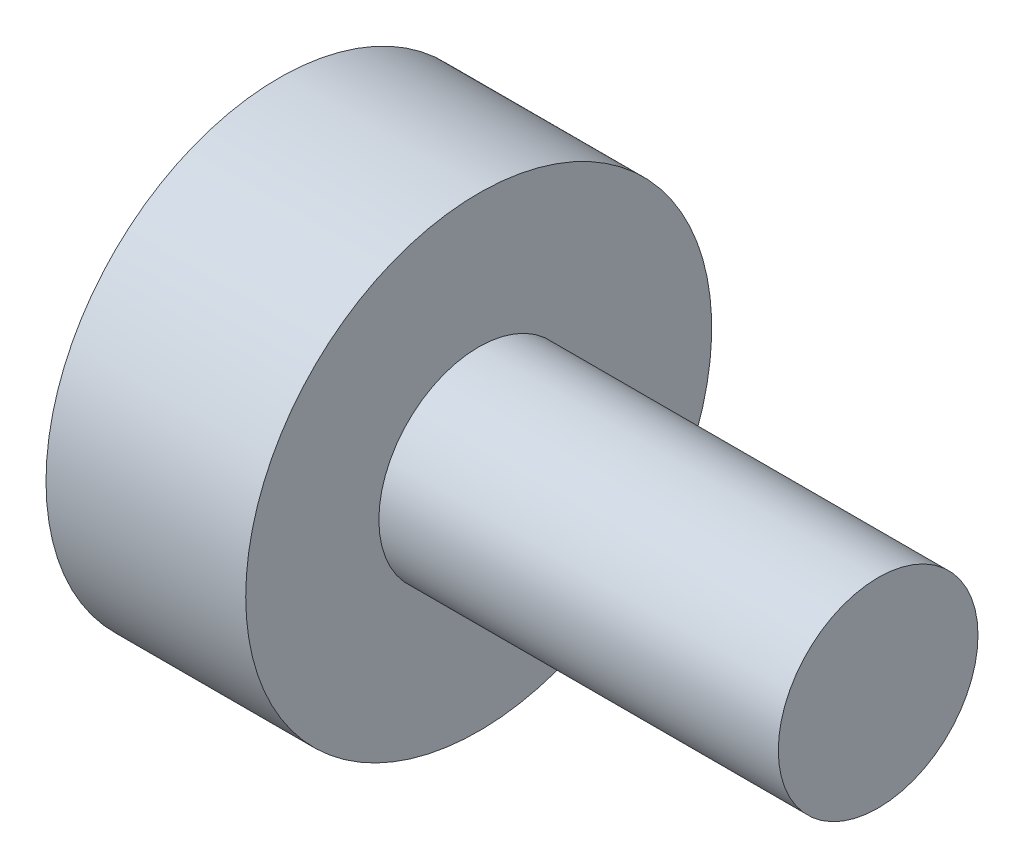
SolidWorks part; units mm, degrees
ref_plane "Спереди" through (0, 0, 0) normal (0, 0, 1) x (1, 0, 0)
ref_plane "Сверху" through (0, 0, 0) normal (0, 1, 0) x (1, 0, 0)
ref_plane "Справа" through (0, 0, 0) normal (1, 0, 0) x (0, 0, -1)
sketch "Эскиз1" plane through (0, 0, 0) normal (0, 0, 1) x (1, 0, 0)
  line L0 (0, 0) -> (100, 0)
  line L1 (0, 0) -> (0, 20)
  line L2 (0, 20) -> (10, 20)
  line L3 (10, 20) -> (10, 35)
  line L4 (10, 35) -> (40, 35)
  line L5 (40, 35) -> (40, 15)
  line L6 (40, 15) -> (100, 15)
  line L7 (100, 0) -> (100, 15)
revolve "Повернуть1" add sketch "Эскиз1" angle 360 about L0
